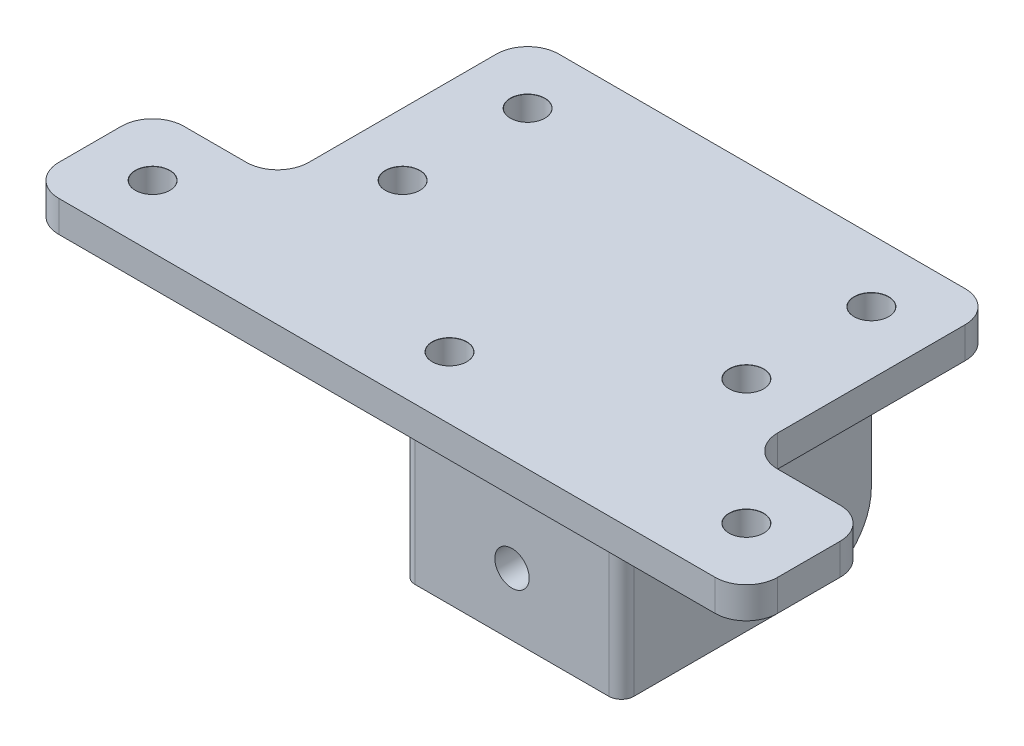
SolidWorks part; units mm, degrees
ref_plane "Front Plane" through (0, 0, 0) normal (0, 0, 1) x (1, 0, 0)
ref_plane "Top Plane" through (0, 0, 0) normal (0, 1, 0) x (1, 0, 0)
ref_plane "Right Plane" through (0, 0, 0) normal (1, 0, 0) x (0, 0, -1)
sketch "Sketch2" plane through (0, 0, 0) normal (0, 1, 0) x (1, 0, 0)
  line L0 (-57.5, 0) -> (57.5, 0)
  line L1 (-55, 0) -> (55, 0) construction
  line L2 (57.5, 0) -> (57.5, 20)
  line L3 (57.5, 20) -> (37.5, 20)
  line L4 (37.5, 20) -> (37.5, 60)
  line L5 (37.5, 60) -> (-37.5, 60)
  line L6 (-37.5, 60) -> (-37.5, 20)
  line L7 (-37.5, 20) -> (-57.5, 20)
  line L8 (-57.5, 20) -> (-57.5, 0)
  line L9 (0, -55) -> (0, 55) construction
  point P6 (0, 0)
  point P12 (0, 60)
  dimension "D1" = 75
  dimension "D2" = 20
  dimension "D3" = 20
  dimension "D4" = 40
extrude "Boss-Extrude1" add sketch "Sketch2" along normal blind 5
sketch "Sketch3" plane through (0, 0, 0) normal (0, -1, 0) x (1, 0, 0)
  line L0 (0, -55) -> (0, 55) construction
  line L1 (-17.5, -20) -> (17.5, -20) construction
  line L2 (-17.5, -20) -> (-17.5, -60) construction
  line L3 (-17.5, -60) -> (17.5, -60) construction
  line L4 (17.5, -20) -> (17.5, -60) construction
  line L5 (-17.5, -20) -> (17.5, -60) construction
  line L6 (-17.5, -60) -> (17.5, -20) construction
  line L7 (37.5, -60) -> (-37.5, -60) construction
  line L8 (57.5, -20) -> (37.5, -20) construction
  line L9 (17.5, -60) -> (17.5, -20)
  line L10 (17.5, -20) -> (-17.5, -20)
  line L11 (-17.5, -20) -> (-17.5, -60)
  line L12 (-17.5, -60) -> (-12.5, -60)
  line L13 (-12.5, -60) -> (-13.0962, -25)
  line L14 (-13.0962, -25) -> (12.5, -25)
  line L15 (12.5, -25) -> (12.5, -60)
  line L16 (12.5, -60) -> (17.5, -60)
  point P0 (0, -40)
  dimension "D1" = 35
  dimension "D2" = 5
  dimension "D3" = 5
extrude "Boss-Extrude2" add sketch "Sketch3" along normal blind 40
sketch "Sketch4" plane through (0, 5, 0) normal (0, 1, 0) x (1, 0, 0)
  line L0 (-37.5, 50) -> (-27.5, 50) construction
  line L1 (-37.5, 60) -> (-37.5, 20) construction
  line L2 (37.5, 60) -> (-37.5, 60) construction
  line L3 (-37.5, 30) -> (-27.5, 30) construction
  line L4 (-37.5, 20) -> (-57.5, 20) construction
  dimension "D1" = 10
  dimension "D2" = 10
  dimension "D3" = 10
hole_wizard "M5 Clearance Hole1" positions "3DSketch1" profile "Sketch5" hole size "M5" standard "ANSI Metric" end condition through all
sketch3d "3DSketch1"
  point P0 (-27.5, 5, -50)
  point P3 (-27.5, 5, -30)
sketch "Sketch5" plane through (-27.5, 5, -50) normal (1, 0, 0) x (0, 0, 1)
  line L0 (0, 0) -> (0, 45)
  line L1 (0, 45) -> (2.75, 45)
  line L2 (2.75, 45) -> (2.75, 0.025)
  line L3 (2.75, 0.025) -> (2.775, 0)
  line L5 (2.775, 0) -> (0, 0)
  line L6 (-2.75, 0.025) -> (-2.775, 0) construction
  line L11 (0, -6.35) -> (0, 107.95) construction
  dimension "Thru Hole Dia." = 5.5
  dimension "Thru Hole Depth" = 45
  dimension "Near C'Sink Dia." = 5.55
  dimension "Near C'Sink Angle" = 90
mirror "Mirror1" about plane through (0, 0, 0) normal (1, 0, 0) of "M5 Clearance Hole1"
sketch "Sketch7" plane through (0, 5, 0) normal (0, 1, 0) x (1, 0, 0)
  line L0 (-57.5, 10) -> (-47.5, 10) construction
  line L1 (-57.5, 20) -> (-57.5, 0) construction
  dimension "D1" = 10
hole_wizard "M5 Clearance Hole2" positions "3DSketch3" profile "Sketch8" hole size "M5" standard "ANSI Metric" end condition through all
sketch3d "3DSketch3"
  point P0 (-47.5, 5, -10)
sketch "Sketch8" plane through (-47.5, 5, -10) normal (1, 0, 0) x (0, 0, 1)
  line L0 (0, 0) -> (0, 45)
  line L1 (0, 45) -> (2.75, 45)
  line L2 (2.75, 45) -> (2.75, 0.025)
  line L3 (2.75, 0.025) -> (2.775, 0)
  line L5 (2.775, 0) -> (0, 0)
  line L6 (-2.75, 0.025) -> (-2.775, 0) construction
  line L11 (0, -6.35) -> (0, 107.95) construction
  dimension "Thru Hole Dia." = 5.5
  dimension "Thru Hole Depth" = 45
  dimension "Near C'Sink Dia." = 5.55
  dimension "Near C'Sink Angle" = 90
mirror "Mirror2" about plane through (0, 0, 0) normal (1, 0, 0) of "M5 Clearance Hole2"
fillet "Fillet1" radius 2 2 edges at (-17.5, -20, -20) (17.5, -20, -20)
sketch "Sketch9" plane through (0, 0, -25) normal (0, 0, -1) x (-1, 0, 0)
  line L0 (0, 0) -> (0, -30) construction
  line L1 (0, 24.75) -> (0, -24.75) construction
  dimension "D1" = 30
hole_wizard "M5 Clearance Hole3" positions "3DSketch4" profile "Sketch10" hole size "M5" standard "ANSI Metric" end condition through all
sketch3d "3DSketch4"
  point P0 (0, -30, -25)
sketch "Sketch10" plane through (0, -30, -25) normal (1, 0, 0) x (0, 1, 0)
  line L0 (0, 0) -> (0, 25)
  line L1 (0, 25) -> (2.75, 25)
  line L2 (2.75, 25) -> (2.75, 0.025)
  line L3 (2.75, 0.025) -> (2.775, 0)
  line L5 (2.775, 0) -> (0, 0)
  line L6 (-2.75, 0.025) -> (-2.775, 0) construction
  line L11 (0, -6.35) -> (0, 107.95) construction
  dimension "Thru Hole Dia." = 5.5
  dimension "Thru Hole Depth" = 25
  dimension "Near C'Sink Dia." = 5.55
  dimension "Near C'Sink Angle" = 90
fillet "Fillet2" radius 5 8 edges at (37.5, 2.5, -20) (-37.5, 2.5, -20) (-37.5, 2.5, -60) (37.5, 2.5, -60) (57.5, 2.5, 0) (57.5, 2.5, -20) (-57.5, 2.5, -20) (-57.5, 2.5, 0)
sketch "Sketch11" plane through (0, 5, 0) normal (0, 1, 0) x (1, 0, 0)
  line L0 (0, 0) -> (0, 10) construction
  line L1 (0, -24.75) -> (0, 24.75) construction
  dimension "D1" = 10
hole_wizard "M5 Clearance Hole4" positions "3DSketch5" profile "Sketch12" hole size "M5" standard "ANSI Metric" end condition through all
sketch3d "3DSketch5"
  point P0 (0, 5, -10)
sketch "Sketch12" plane through (0, 5, -10) normal (1, 0, 0) x (0, 0, 1)
  line L0 (0, 0) -> (0, 45)
  line L1 (0, 45) -> (2.75, 45)
  line L2 (2.75, 45) -> (2.75, 0.025)
  line L3 (2.75, 0.025) -> (2.775, 0)
  line L5 (2.775, 0) -> (0, 0)
  line L6 (-2.75, 0.025) -> (-2.775, 0) construction
  line L11 (0, -6.35) -> (0, 107.95) construction
  dimension "Thru Hole Dia." = 5.5
  dimension "Thru Hole Depth" = 45
  dimension "Near C'Sink Dia." = 5.55
  dimension "Near C'Sink Angle" = 90
sketch "Sketch13" plane through (-17.5, 0, 0) normal (-1, 0, 0) x (0, 0, 1)
  line L0 (-50, -40) -> (-50, -30) construction
  line L1 (-22, -40) -> (-60, -40) construction
  line L2 (-60, -40) -> (-60, 0) construction
  dimension "D1" = 10
  dimension "D2" = 10
hole_wizard "M5 Clearance Hole5" positions "3DSketch6" profile "Sketch14" hole size "M5" standard "ANSI Metric" end condition through all
sketch3d "3DSketch6"
  point P0 (-17.5, -30, -50)
sketch "Sketch14" plane through (-17.5, -30, -50) normal (0, 1, 0) x (0, 0, 1)
  line L0 (0, 0) -> (0, 75)
  line L1 (0, 75) -> (2.75, 75)
  line L2 (2.75, 75) -> (2.75, 0.025)
  line L3 (2.75, 0.025) -> (2.775, 0)
  line L5 (2.775, 0) -> (0, 0)
  line L6 (-2.75, 0.025) -> (-2.775, 0) construction
  line L11 (0, -6.35) -> (0, 107.95) construction
  dimension "Thru Hole Dia." = 5.5
  dimension "Thru Hole Depth" = 75
  dimension "Near C'Sink Dia." = 5.55
  dimension "Near C'Sink Angle" = 90
fillet "Fillet3" radius 10 2 edges at (-15, -40, -60) (15, -40, -60)
